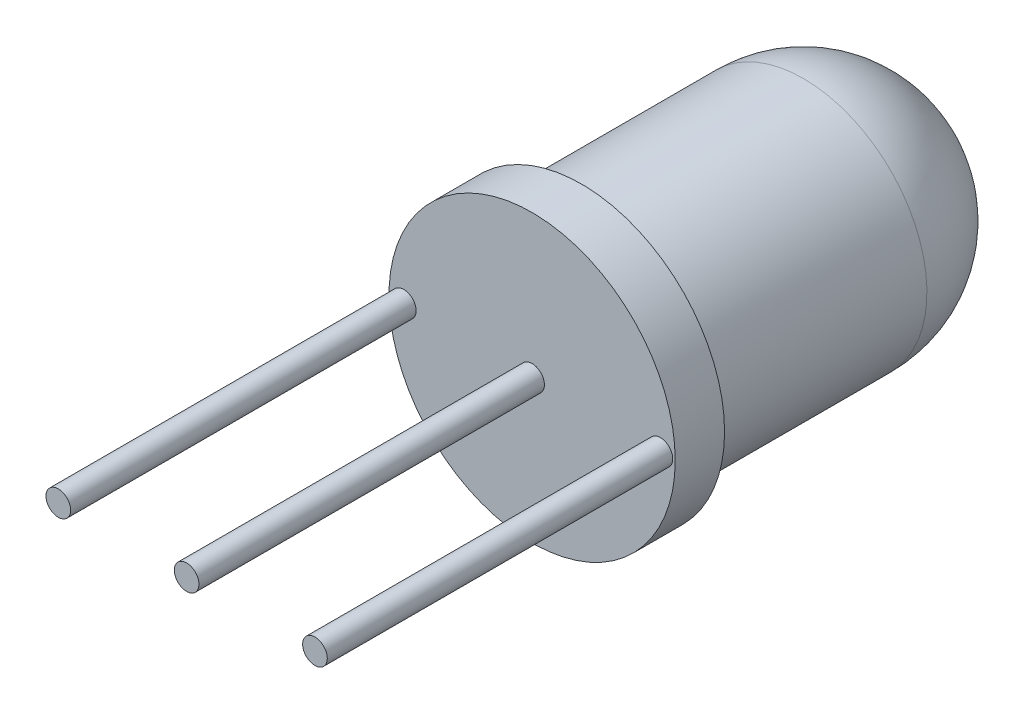
SolidWorks part; units mm, degrees
ref_plane "前视基准面" through (0, 0, 0) normal (0, 0, 1) x (1, 0, 0)
ref_plane "上视基准面" through (0, 0, 0) normal (0, 1, 0) x (1, 0, 0)
ref_plane "右视基准面" through (0, 0, 0) normal (1, 0, 0) x (0, 0, -1)
sketch "草图1" plane through (0, 0, 0) normal (0, 0, 1) x (1, 0, 0)
  circle A0 centre (0, 0) radius 2.5
  dimension "D1" = 5
extrude "拉伸1" add sketch "草图1" along normal blind 5.5
sketch "草图2" plane through (0, 0, 5.5) normal (0, 0, 1) x (1, 0, 0)
  circle A0 centre (0, 0) radius 2.9
  dimension "D1" = 5.8
extrude "拉伸2" add sketch "草图2" against normal blind 1
sketch "草图3" plane through (0, 0, 4.5) normal (0, 0, -1) x (-1, 0, 0)
  line L0 (0, 2.011) -> (0, -2.1052) construction
  line L1 (-2.1813, 0) -> (2.3335, 0) construction
  circle A0 centre (-1.27, 0) radius 0.25
  circle A1 centre (1.27, 0) radius 0.25
  dimension "D1" = 0.5
  dimension "D2" = 2.54
sketch "草图5" plane through (0, 0, 0) normal (1, 0, 0) x (0, 0, -1)
  line L0 (0, 2.5) -> (0, 0)
  line L1 (2.5, 0) -> (0, 0)
  arc A0 (0, 2.5) -> (2.5, 0) centre (0, 0) cw
  dimension "D1" = 2.5
revolve "旋转2" add sketch "草图5" angle 360 about L1
sketch "草图6" plane through (0, 0, 5.5) normal (0, 0, 1) x (1, 0, 0)
  line L0 (2.9, 0) -> (-2.9, 0)
  line L1 (0, -3.253) -> (0, 3.6113) construction
  circle A0 centre (0, 0) radius 2.9 construction
  circle A1 centre (0, 0) radius 0.25
  circle A2 centre (2.6, 0) radius 0.25
  circle A3 centre (-2.6, 0) radius 0.25
  dimension "D1" = 0.5
  dimension "D2" = 0.5
  dimension "D3" = 2.6
extrude "凸台-拉伸1" add sketch "草图6" along normal blind 7 contours L0 A2 | L0 A2 | A1 L1 L0 | L0 L1 A1 | L1 L0 A1 | L1 A1 L0 | A3 L0 | A3 L0
